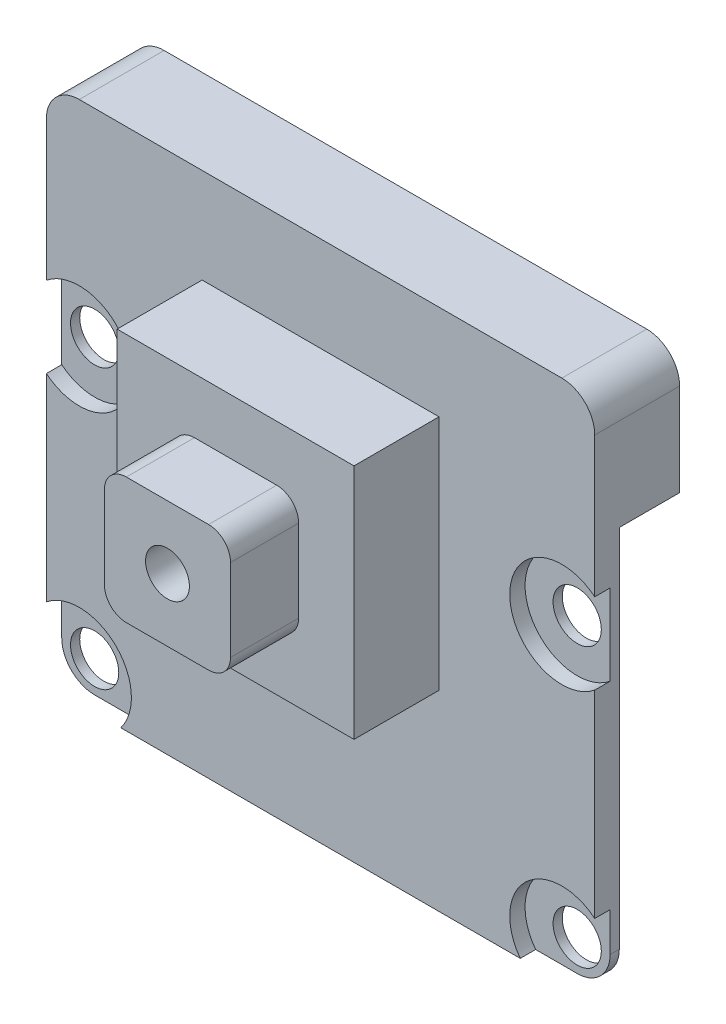
SolidWorks part; units mm, degrees
ref_plane "Front Plane" through (0, 0, 0) normal (0, 0, 1) x (1, 0, 0)
ref_plane "Top Plane" through (0, 0, 0) normal (0, 1, 0) x (1, 0, 0)
ref_plane "Right Plane" through (0, 0, 0) normal (1, 0, 0) x (0, 0, -1)
sketch "Sketch1" plane through (0, 0, 0) normal (0, 0, 1) x (1, 0, 0)
  line L0 (0, 2.2016) -> (0, 0) construction
  line L1 (-12.5, -11.93) -> (12.5, -11.93)
  line L2 (-12.5, -11.93) -> (-12.5, 11.93)
  line L3 (-12.5, 11.93) -> (12.5, 11.93)
  line L4 (12.5, -11.93) -> (12.5, 11.93)
  line L5 (-12.5, -11.93) -> (12.5, 11.93) construction
  line L6 (-12.5, 11.93) -> (12.5, -11.93) construction
  line L7 (-11, 2.2016) -> (11, 2.2016) construction
  line L8 (-11, 2.2016) -> (-11, -10.4984) construction
  line L9 (-11, -10.4984) -> (11, -10.4984) construction
  line L10 (11, 2.2016) -> (11, -10.4984) construction
  line L12 (-5.4, 7.6016) -> (5.4, 7.6016) construction
  line L13 (-5.4, 7.6016) -> (-5.4, -3.1984) construction
  line L14 (-5.4, -3.1984) -> (5.4, -3.1984) construction
  line L15 (5.4, 7.6016) -> (5.4, -3.1984) construction
  line L16 (-1.875, 5.0766) -> (1.875, 5.0766) construction
  line L17 (-2.875, 4.0766) -> (-2.875, 0.3266) construction
  line L18 (-1.875, -0.6734) -> (1.875, -0.6734) construction
  line L19 (2.875, 4.0766) -> (2.875, 0.3266) construction
  circle A0 centre (-11, 2.2016) radius 1.1 construction
  circle A1 centre (-11, 2.2016) radius 2.375 construction
  circle A2 centre (-11, -10.4984) radius 1.1 construction
  circle A3 centre (11, -10.4984) radius 1.1
  circle A4 centre (11, 2.2016) radius 1.1 construction
  circle A5 centre (11, 2.2016) radius 2.375 construction
  circle A6 centre (11, -10.4984) radius 2.375 construction
  circle A7 centre (-11, -10.4984) radius 2.375 construction
  arc A8 (-2.875, 0.3266) -> (-1.875, -0.6734) centre (-1.875, 0.3266) ccw construction
  arc A9 (1.875, -0.6734) -> (2.875, 0.3266) centre (1.875, 0.3266) ccw construction
  arc A10 (1.875, 5.0766) -> (2.875, 4.0766) centre (1.875, 4.0766) cw construction
  arc A11 (-1.875, 5.0766) -> (-2.875, 4.0766) centre (-1.875, 4.0766) ccw construction
  circle A12 centre (0, 2.2016) radius 1 construction
  point P0 (0, 0)
  point P21 (0, -3.1984)
  point P27 (-5.4, 2.2016)
  point P30 (0, -0.6734)
  point P31 (2.875, 2.2016)
  dimension "D3" = 2.2
  dimension "D4" = 4.75
  dimension "D8" = 1
  dimension "D9" = 2
  dimension "D1" = 23.86
  dimension "D2" = 25
  dimension "D5" = 10.8
  dimension "D6" = 7.3
  dimension "D7" = 5.75
  dimension "D10" = 22
extrude "Boss-Extrude1" add sketch "Sketch1" along normal blind 1.12 contours L3 L4 L1 L2
sketch "Sketch4" plane through (0, 0, 1.12) normal (0, 0, 1) x (1, 0, 0)
  line L0 (-5.4, -3.1984) -> (5.4, -3.1984) construction
  line L1 (5.4, 7.6016) -> (5.4, -3.1984) construction
  line L2 (-5.4, 7.6016) -> (-5.4, -3.1984) construction
  line L3 (-5.4, 7.6016) -> (5.4, 7.6016) construction
  line L4 (-5.4, -3.1984) -> (5.4, -3.1984)
  line L5 (5.4, 7.6016) -> (5.4, -3.1984)
  line L6 (-5.4, 7.6016) -> (-5.4, -3.1984)
  line L7 (-5.4, 7.6016) -> (5.4, 7.6016)
extrude "Boss-Extrude2" add sketch "Sketch4" along normal blind 3.875
sketch "Sketch5" plane through (0, 0, 1.12) normal (0, 0, 1) x (1, 0, 0)
  circle A0 centre (11, 2.2016) radius 2.375 construction
  circle A1 centre (11, -10.4984) radius 2.375 construction
  circle A2 centre (-11, -10.4984) radius 2.375 construction
  circle A3 centre (-11, 2.2016) radius 2.375 construction
  circle A4 centre (11, 2.2016) radius 2.375
  circle A5 centre (11, -10.4984) radius 2.375
  circle A6 centre (-11, -10.4984) radius 2.375
  circle A7 centre (-11, 2.2016) radius 2.375
extrude "Cut-Extrude1" cut sketch "Sketch5" against normal blind 0.7
sketch "Sketch6" plane through (0, 0, 1.12) normal (0, 0, 1) x (1, 0, 0)
  circle A0 centre (11, 2.2016) radius 1.1 construction
  circle A1 centre (11, -10.4984) radius 1.1 construction
  circle A2 centre (-11, -10.4984) radius 1.1 construction
  circle A3 centre (-11, 2.2016) radius 1.1 construction
  circle A4 centre (11, 2.2016) radius 1.1
  circle A5 centre (11, -10.4984) radius 1.1
  circle A6 centre (-11, -10.4984) radius 1.1
  circle A7 centre (-11, 2.2016) radius 1.1
extrude "Cut-Extrude2" cut sketch "Sketch6" against normal up to next
sketch "Sketch8" plane through (0, 0, 1.12) normal (0, 0, 1) x (1, 0, 0)
  line L0 (2.875, 4.0766) -> (2.875, 0.3266) construction
  line L1 (-1.875, -0.6734) -> (1.875, -0.6734) construction
  line L2 (-2.875, 4.0766) -> (-2.875, 0.3266) construction
  line L3 (-1.875, 5.0766) -> (1.875, 5.0766) construction
  line L4 (2.875, 4.0766) -> (2.875, 0.3266)
  line L5 (-1.875, -0.6734) -> (1.875, -0.6734)
  line L6 (-2.875, 4.0766) -> (-2.875, 0.3266)
  line L7 (-1.875, 5.0766) -> (1.875, 5.0766)
  arc A0 (2.875, 4.0766) -> (1.875, 5.0766) centre (1.875, 4.0766) ccw construction
  arc A1 (1.875, -0.6734) -> (2.875, 0.3266) centre (1.875, 0.3266) ccw construction
  arc A2 (-2.875, 0.3266) -> (-1.875, -0.6734) centre (-1.875, 0.3266) ccw construction
  arc A3 (-1.875, 5.0766) -> (-2.875, 4.0766) centre (-1.875, 4.0766) ccw construction
  arc A4 (2.875, 4.0766) -> (1.875, 5.0766) centre (1.875, 4.0766) ccw
  arc A5 (1.875, -0.6734) -> (2.875, 0.3266) centre (1.875, 0.3266) ccw
  arc A6 (-2.875, 0.3266) -> (-1.875, -0.6734) centre (-1.875, 0.3266) ccw
  arc A7 (-1.875, 5.0766) -> (-2.875, 4.0766) centre (-1.875, 4.0766) ccw
  circle A8 centre (0, 2.2016) radius 1 construction
  circle A9 centre (0, 2.2016) radius 1
extrude "Boss-Extrude3" add sketch "Sketch8" along normal blind 6.98
sketch "Sketch9" plane through (0, 0, 0) normal (0, 0, -1) x (-1, 0, 0)
  line L0 (12.5, -11.93) -> (12.5, 11.93) construction
  line L1 (-12.5, 11.93) -> (12.5, 11.93)
  line L2 (-12.5, 11.93) -> (-12.5, 6.22)
  line L3 (-12.5, 6.22) -> (12.5, 6.22)
  line L4 (12.5, 11.93) -> (12.5, 6.22)
  dimension "D1" = 5.71
extrude "Boss-Extrude4" add sketch "Sketch9" along normal blind 2.75
fillet "Fillet1" radius 1.5 4 edges at (12.5, -11.93, 0.21) (12.5, 11.93, -0.815) (-12.5, 11.93, -0.815) (-12.5, -11.93, 0.21)
